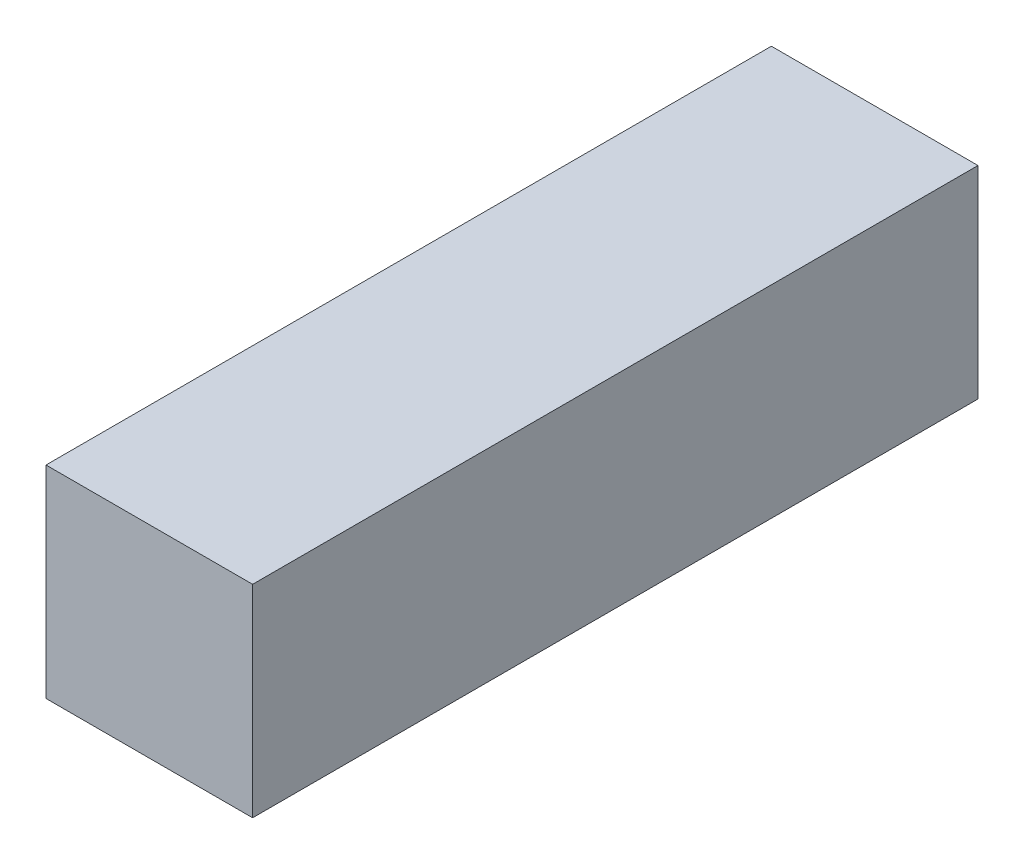
SolidWorks part; units mm, degrees
ref_plane "前视基准面" through (0, 0, 0) normal (0, 0, 1) x (1, 0, 0)
ref_plane "上视基准面" through (0, 0, 0) normal (0, 1, 0) x (1, 0, 0)
ref_plane "右视基准面" through (0, 0, 0) normal (1, 0, 0) x (0, 0, -1)
sketch "草图1" plane through (0, 0, 0) normal (0, 1, 0) x (1, 0, 0)
  line L1 (-23.5, -82.5) -> (23.5, -82.5)
  line L2 (-23.5, -82.5) -> (-23.5, 82.5)
  line L3 (-23.5, 82.5) -> (23.5, 82.5)
  line L4 (23.5, -82.5) -> (23.5, 82.5)
  line L5 (-23.5, -82.5) -> (23.5, 82.5) construction
  line L6 (-23.5, 82.5) -> (23.5, -82.5) construction
  point P0 (0, 0)
  dimension "D1" = 165
  dimension "D2" = 47
extrude "凸台-拉伸1" add sketch "草图1" along normal blind 46
